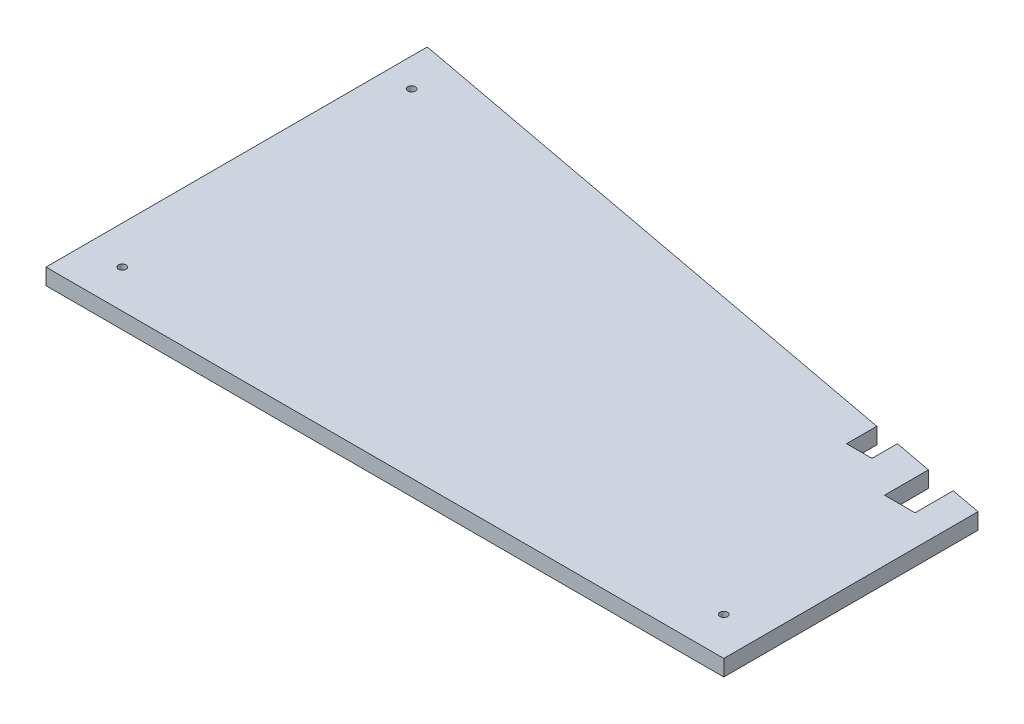
SolidWorks part; units mm, degrees
material "Balsa"
ref_plane "Front Plane" through (0, 0, 0) normal (0, 0, 1) x (1, 0, 0)
ref_plane "Top Plane" through (0, 0, 0) normal (0, 1, 0) x (1, 0, 0)
ref_plane "Right Plane" through (0, 0, 0) normal (1, 0, 0) x (0, 0, -1)
sketch "Sketch2" plane through (0, 0, 0) normal (0, 1, 0) x (1, 0, 0)
  line L0 (0, 0) -> (266.65, 0)
  line L1 (266.65, 0) -> (266.65, 100)
  line L2 (266.65, 100) -> (254.65, 102.2501)
  line L4 (242.6501, 104.5003) -> (242.6501, 87.2152)
  line L5 (242.6501, 87.2152) -> (254.65, 87.2501)
  line L6 (254.65, 87.2501) -> (254.65, 102.2501)
  line L7 (242.6501, 104.5003) -> (227.6501, 107.3129)
  line L8 (227.6501, 97.3129) -> (217.6501, 97.2838)
  line L9 (217.6501, 97.2838) -> (217.6501, 109.1881)
  line L10 (227.6501, 97.3129) -> (227.6501, 107.3129)
  line L11 (217.6501, 109.1881) -> (0, 150)
  line L16 (0, 150) -> (0, 0)
  circle A2 centre (15, 15) radius 1.5
  circle A3 centre (251.65, 15) radius 1.5
  circle A4 centre (11.1969, 132.639) radius 1.5
  point P10 (0, 0)
  point P12 (0, 0)
  dimension "D14" = 3
  dimension "D15" = 3
  dimension "D16" = 3
  dimension "D1" = 150
  dimension "D2" = 100
  dimension "D3" = 266.65
  dimension "D4" = 12
  dimension "D5" = 12
  dimension "D6" = 15
  dimension "D7" = 10
  dimension "D8" = 10
  dimension "D9" = 15
  dimension "D18" = 15
  dimension "D20" = 15
  dimension "D21" = 15
  dimension "D22" = 15
extrude "Boss-Extrude1" add sketch "Sketch2" along normal blind 6.35
